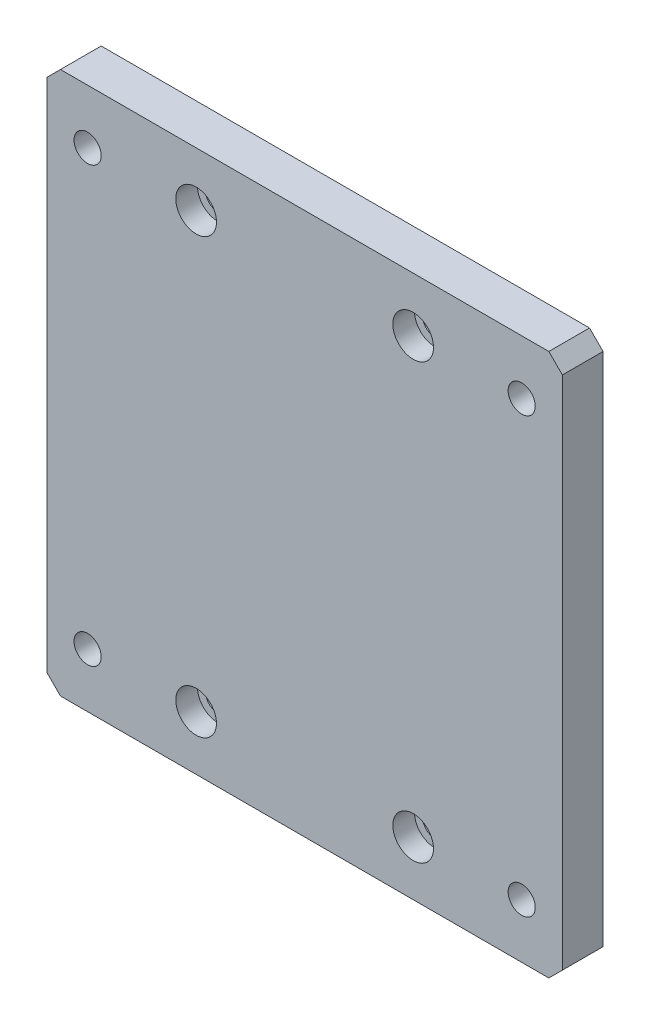
SolidWorks part; units mm, degrees
ref_plane "Alzado" through (0, 0, 0) normal (0, 0, 1) x (1, 0, 0)
ref_plane "Planta" through (0, 0, 0) normal (0, 1, 0) x (1, 0, 0)
ref_plane "Vista lateral" through (0, 0, 0) normal (1, 0, 0) x (0, 0, -1)
sketch "Croquis1" plane through (0, 0, 0) normal (0, 0, 1) x (1, 0, 0)
  line L1 (-95, 100) -> (95, 100)
  line L2 (-95, 100) -> (-95, -100)
  line L3 (-95, -100) -> (95, -100)
  line L4 (95, 100) -> (95, -100)
  line L5 (-95, 100) -> (95, -100) construction
  line L6 (-95, -100) -> (95, 100) construction
  point P0 (0, 0)
  dimension "D1" = 190
  dimension "D2" = 200
extrude "Saliente-Extruir1" add sketch "Croquis1" along normal blind 15
sketch "Croquis2" plane through (0, 0, 15) normal (0, 0, 1) x (1, 0, 0)
  line L1 (-40, -80) -> (40, -80) construction
  line L2 (-40, -80) -> (-40, 80) construction
  line L3 (-40, 80) -> (40, 80) construction
  line L4 (40, -80) -> (40, 80) construction
  line L5 (-40, -80) -> (40, 80) construction
  line L6 (-40, 80) -> (40, -80) construction
  circle A0 centre (-40, 80) radius 4
  circle A1 centre (40, 80) radius 4
  circle A2 centre (40, -80) radius 4
  circle A3 centre (-40, -80) radius 4
  point P0 (0, 0)
  dimension "D3" = 8
  dimension "D4" = 8
  dimension "D5" = 8
  dimension "D6" = 8
  dimension "D1" = 80
  dimension "D2" = 160
extrude "Cortar-Extruir1" cut sketch "Croquis2" against normal through all
sketch "Croquis3" plane through (0, 0, 15) normal (0, 0, 1) x (1, 0, 0)
  line L0 (-95, 100) -> (-95, -100) construction
  line L1 (-80, 80) -> (80, 80) construction
  line L2 (-80, 80) -> (-80, -80) construction
  line L3 (-80, -80) -> (80, -80) construction
  line L4 (80, 80) -> (80, -80) construction
  line L5 (-80, 80) -> (80, -80) construction
  line L6 (-80, -80) -> (80, 80) construction
  line L7 (95, 100) -> (-95, 100) construction
  circle A0 centre (-80, 80) radius 5
  circle A1 centre (80, 80) radius 5
  circle A2 centre (80, -80) radius 5
  circle A3 centre (-80, -80) radius 5
  point P0 (0, 0)
  dimension "D3" = 10
  dimension "D1" = 15
  dimension "D2" = 20
extrude "Cortar-Extruir2" cut sketch "Croquis3" against normal through all
chamfer "Chaflán1" distance 5 angle 45 4 edges at (95, 100, 7.5) (95, -100, 7.5) (-95, 100, 7.5) (-95, -100, 7.5)
hole_wizard "Refrentado para tornillo tapón con cabeza de clavija de M81" positions "Croquis6" profile "Croquis5" counterbore size "M8" standard "Ansi Metric" end condition through all
sketch "Croquis6" plane through (0, 0, 15) normal (0, 0, 1) x (1, 0, 0)
  point P0 (40, 80)
  point P3 (-40, 80)
  point P6 (-40, -80)
  point P9 (40, -80)
sketch "Croquis5" plane through (40, 80, 15) normal (1, 0, 0) x (0, -1, 0)
  line L0 (0, 0) -> (0, 15)
  line L1 (0, 15) -> (4.5, 15)
  line L3 (4.5, 15) -> (4.5, 8)
  line L4 (4.5, 8) -> (7.5, 8)
  line L5 (7.5, 8) -> (7.5, 0)
  line L7 (7.5, 0) -> (0, 0)
  line L11 (0, -6.35) -> (0, 107.95) construction
  dimension "Diámetro de taladro hasta el siguiente" = 9
  dimension "Profundidad de taladro hasta el siguiente" = 15
  dimension "Diámetro de refrentado" = 15
  dimension "Profundidad de refrentado" = 8
